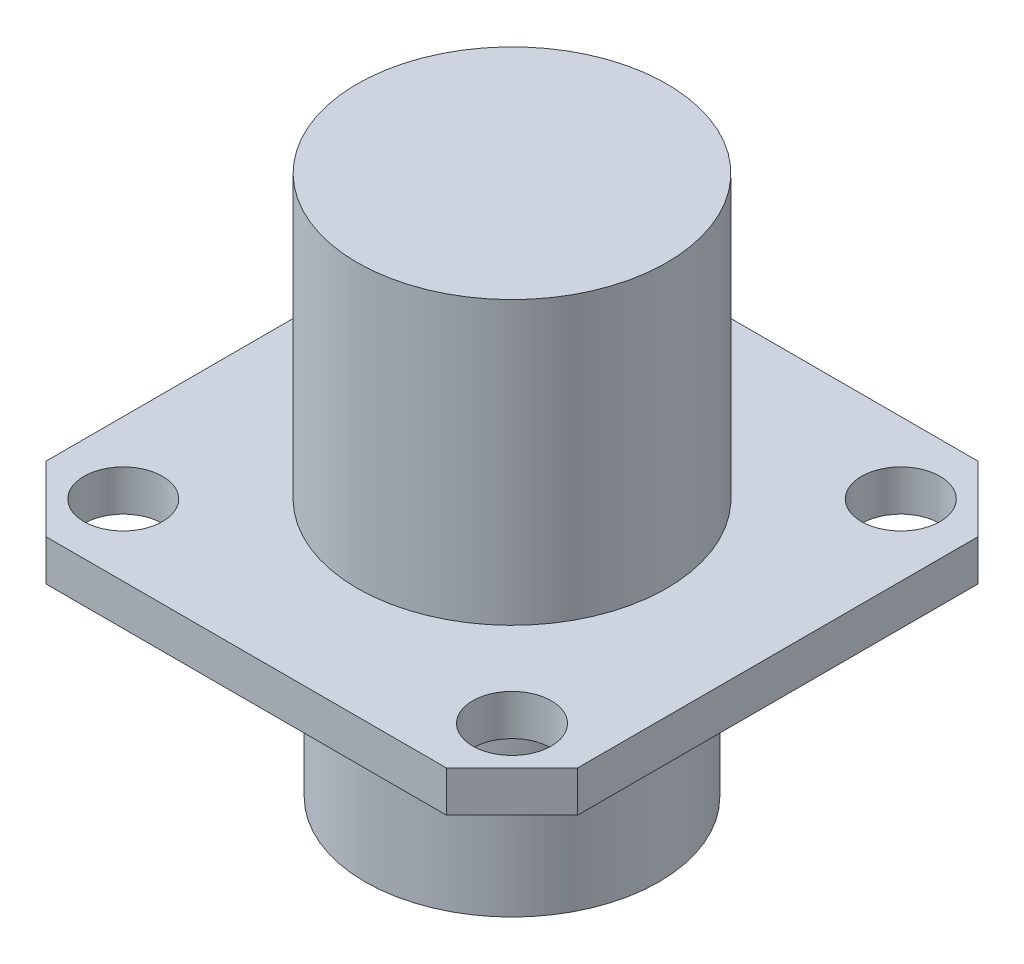
SolidWorks part; units mm, degrees
material "6061-T6 (SS)"
ref_plane "Front Plane" through (0, 0, 0) normal (0, 0, 1) x (1, 0, 0)
ref_plane "Top Plane" through (0, 0, 0) normal (0, 1, 0) x (1, 0, 0)
ref_plane "Right Plane" through (0, 0, 0) normal (1, 0, 0) x (0, 0, -1)
sketch "Sketch1" plane through (0, 0, 0) normal (0, 1, 0) x (1, 0, 0)
  line L1 (-10.3124, 10.3124) -> (10.3124, 10.3124)
  line L2 (-10.3124, 10.3124) -> (-10.3124, -10.3124)
  line L3 (-10.3124, -10.3124) -> (10.3124, -10.3124)
  line L4 (10.3124, 10.3124) -> (10.3124, -10.3124)
  line L5 (-10.3124, 10.3124) -> (10.3124, -10.3124) construction
  line L6 (-10.3124, -10.3124) -> (10.3124, 10.3124) construction
  point P0 (0, 0)
  dimension "D1" = 20.6248
extrude "Boss-Extrude1" add sketch "Sketch1" along normal blind 1.5875
chamfer "Chamfer1" distance 2.54 angle 45 4 edges at (-10.3124, 0.7937, -10.3124) (10.3124, 0.7937, -10.3124) (10.3124, 0.7937, 10.3124) (-10.3124, 0.7937, 10.3124)
sketch "Sketch2" plane through (0, 1.5875, 0) normal (0, 1, 0) x (1, 0, 0)
  line L1 (-7.5438, 7.5438) -> (7.5438, 7.5438) construction
  line L2 (-7.5438, 7.5438) -> (-7.5438, -7.5438) construction
  line L3 (-7.5438, -7.5438) -> (7.5438, -7.5438) construction
  line L4 (7.5438, 7.5438) -> (7.5438, -7.5438) construction
  line L5 (-7.5438, 7.5438) -> (7.5438, -7.5438) construction
  line L6 (-7.5438, -7.5438) -> (7.5438, 7.5438) construction
  circle A0 centre (-7.5438, 7.5438) radius 1.524
  circle A1 centre (7.5438, 7.5438) radius 1.524
  circle A2 centre (7.5438, -7.5438) radius 1.524
  circle A3 centre (-7.5438, -7.5438) radius 1.524
  point P0 (0, 0)
  dimension "D2" = 3.048
  dimension "D1" = 15.0876
extrude "Cut-Extrude1" cut sketch "Sketch2" against normal through all
sketch "Sketch3" plane through (0, 1.5875, 0) normal (0, 1, 0) x (1, 0, 0)
  circle A0 centre (0, 0) radius 6.0071
  dimension "D1" = 12.0142
extrude "Boss-Extrude2" add sketch "Sketch3" along normal blind 10.9474
sketch "Sketch4" plane through (0, 0, 0) normal (0, -1, 0) x (1, 0, 0)
  circle A0 centre (0, 0) radius 5.7023
  dimension "D1" = 11.4046
extrude "Boss-Extrude3" add sketch "Sketch4" along normal blind 8.4328
